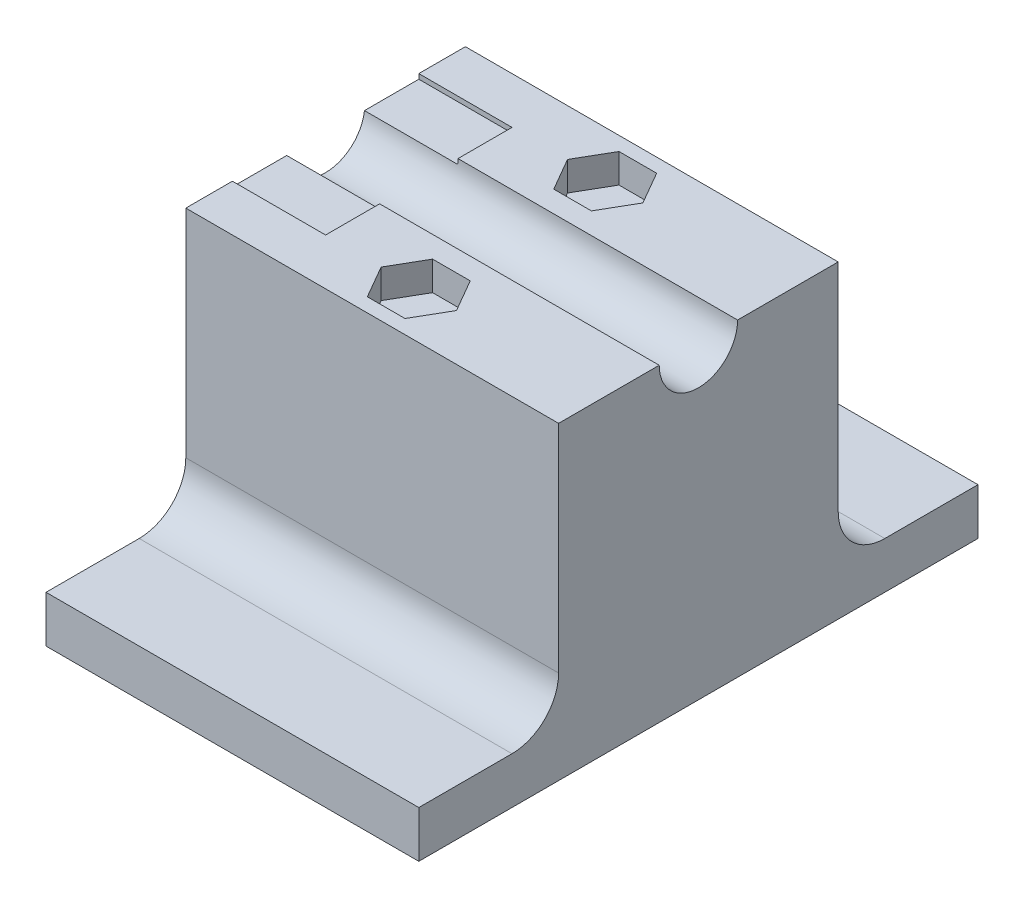
SolidWorks part; units mm, degrees
ref_plane "Front Plane" through (0, 0, 0) normal (0, 0, 1) x (1, 0, 0)
ref_plane "Top Plane" through (0, 0, 0) normal (0, 1, 0) x (1, 0, 0)
ref_plane "Right Plane" through (0, 0, 0) normal (1, 0, 0) x (0, 0, -1)
sketch "Sketch1" plane through (0, 0, 0) normal (0, 1, 0) x (1, 0, 0)
  line L1 (-20, -15) -> (20, -15)
  line L2 (-20, -15) -> (-20, 15)
  line L3 (-20, 15) -> (20, 15)
  line L4 (20, -15) -> (20, 15)
  point P5 (0, -15)
  point P9 (20, 0)
  dimension "D1" = 40
  dimension "D2" = 30
extrude "Boss-Extrude1" add sketch "Sketch1" along normal blind 33.2
sketch "Sketch2" plane through (-20, 0, 0) normal (-1, 0, 0) x (0, 0, 1)
  line L0 (-15, 33.2) -> (15, 33.2) construction
  circle A0 centre (0, 33.2) radius 4.205
  dimension "D1" = 8.41
extrude "Cut-Extrude1" cut sketch "Sketch2" against normal through all
sketch "Sketch3" plane through (0, 33.2, 0) normal (0, 1, 0) x (1, 0, 0)
  line L0 (20, 15) -> (-20, 15) construction
  line L1 (2.0207, 6.5) -> (4.0415, 10)
  line L2 (4.0415, 10) -> (2.0207, 13.5)
  line L3 (2.0207, 13.5) -> (-2.0207, 13.5)
  line L4 (-2.0207, 13.5) -> (-4.0415, 10)
  line L5 (-4.0415, 10) -> (-2.0207, 6.5)
  line L6 (-2.0207, 6.5) -> (2.0207, 6.5)
  circle A0 centre (0, 10) radius 3.5 construction
  point P11 (0, 15)
  dimension "D1" = 5
  dimension "D2" = 7
extrude "Cut-Extrude2" cut sketch "Sketch3" against normal blind 3.12
mirror "Mirror1" about plane through (0, 0, 0) normal (0, 0, 1) of "Cut-Extrude2"
sketch "Sketch4" plane through (20, 0, 0) normal (1, 0, 0) x (0, 0, -1)
  line L0 (-15, 0) -> (15, 0) construction
  line L1 (-30, 0) -> (30, 0)
  line L2 (-30, 0) -> (-30, 5)
  line L3 (-30, 5) -> (30, 5)
  line L4 (30, 0) -> (30, 5)
  point P4 (0, 0)
  dimension "D1" = 60
  dimension "D2" = 5
extrude "Boss-Extrude2" add sketch "Sketch4" against normal up to surface (40 mm away) up to face at (-20, 21.4325, 0)
fillet "Fillet1" radius 5 2 edges at (0, 5, -15) (0, 5, 15)
sketch "Sketch5" plane through (-20, 0, 0) normal (-1, 0, 0) x (0, 0, 1)
  line L1 (-10, 33.725) -> (10, 33.725)
  line L2 (-10, 33.725) -> (-10, 32.675)
  line L3 (-10, 32.675) -> (10, 32.675)
  line L4 (10, 33.725) -> (10, 32.675)
  line L5 (-10, 33.725) -> (10, 32.675) construction
  line L6 (-10, 32.675) -> (10, 33.725) construction
  arc A0 (-4.205, 33.2) -> (4.205, 33.2) centre (0, 33.2) ccw construction
  arc A1 (-4.205, 33.2) -> (4.205, 33.2) centre (0, 33.2) ccw construction
  dimension "D1" = 1.05
  dimension "D2" = 20
extrude "Cut-Extrude3" cut sketch "Sketch5" against normal blind 10
